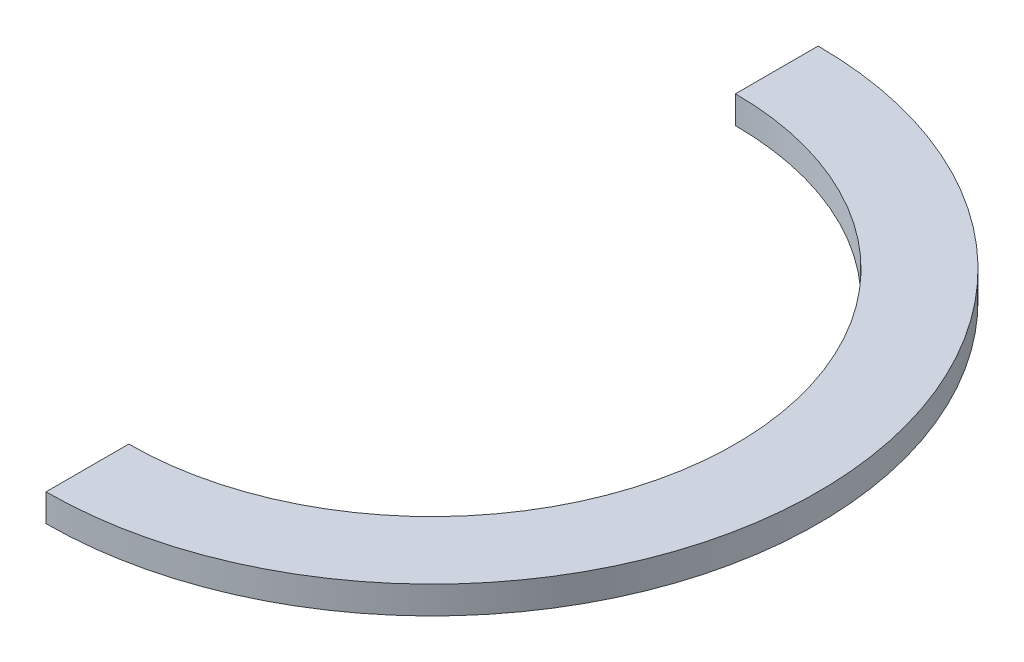
SolidWorks part; units mm, degrees
ref_plane "Front Plane" through (0, 0, 0) normal (0, 0, 1) x (1, 0, 0)
ref_plane "Top Plane" through (0, 0, 0) normal (0, 1, 0) x (1, 0, 0)
ref_plane "Right Plane" through (0, 0, 0) normal (1, 0, 0) x (0, 0, -1)
sketch "Sketch1" plane through (0, 0, 0) normal (0, 1, 0) x (1, 0, 0)
  line L0 (0, 14) -> (0, -14)
  arc A0 (0, -11) -> (0, 11) centre (0, 0) ccw
  arc A1 (0, -14) -> (0, 14) centre (0, 0) ccw
  dimension "D1" = 22
  dimension "D2" = 3
extrude "Boss-Extrude1" add sketch "Sketch1" along normal blind 1 contours L0 A1 A0
